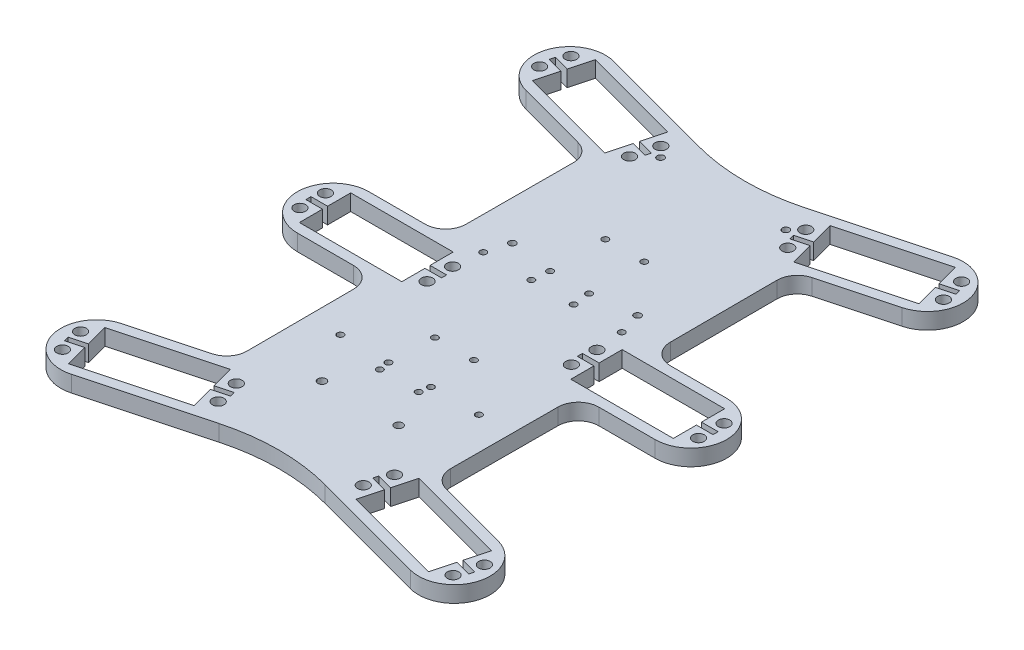
SolidWorks part; units mm, degrees
ref_plane "Front Plane" through (0, 0, 0) normal (0, 0, 1) x (1, 0, 0)
ref_plane "Top Plane" through (0, 0, 0) normal (0, 1, 0) x (1, 0, 0)
ref_plane "Right Plane" through (0, 0, 0) normal (1, 0, 0) x (0, 0, -1)
sketch "Sketch1" plane through (0, 0, 0) normal (0, 1, 0) x (1, 0, 0)
  line L0 (0, 32.1883) -> (0, -21.4181) construction
  line L1 (0, 0) -> (27.1703, 0) construction
  line L2 (-70, 14) -> (-40, 14)
  line L3 (-40, 14) -> (-39.8161, 70)
  line L4 (-39.8161, 70) -> (-73.6235, 79.0587)
  line L5 (-66.3765, 106.1046) -> (0, 88.3191)
  line L10 (-66.3765, 106.1046) -> (-73.6235, 79.0587) construction
  line L12 (-70, 14) -> (-70, -14) construction
  line L14 (-66.3765, -106.1046) -> (0, -88.3191)
  line L15 (-39.8161, -70) -> (-73.6235, -79.0587)
  line L16 (-40, -14) -> (-39.8161, -70)
  line L17 (-70, -14) -> (-40, -14)
  line L18 (66.3765, -106.1046) -> (0, -88.3191)
  line L19 (66.3765, 106.1046) -> (0, 88.3191)
  line L20 (70, 14) -> (70, -14) construction
  line L21 (66.3765, 106.1046) -> (73.6235, 79.0587) construction
  line L22 (70, -14) -> (40, -14)
  line L23 (40, -14) -> (39.8161, -70)
  line L24 (39.8161, -70) -> (73.6235, -79.0587)
  line L25 (39.8161, 70) -> (73.6235, 79.0587)
  line L26 (40, 14) -> (39.8161, 70)
  line L27 (70, 14) -> (40, 14)
  line L28 (-70.4609, 103.1096) -> (-75.6631, 83.6945)
  line L29 (-75.6631, 83.6945) -> (-36.9295, 73.3159)
  line L30 (-36.9295, 73.3159) -> (-31.7272, 92.731)
  line L31 (-31.7272, 92.731) -> (-70.4609, 103.1096)
  line L32 (-51.094, 97.9203) -> (-56.2963, 78.5052) construction
  line L33 (-70, 92.5816) -> (-73.062, 93.4021) construction
  line L34 (-53.12, 10.05) -> (-53.12, -10.05) construction
  line L35 (-73.17, 10.05) -> (-33.07, 10.05)
  line L36 (-73.17, 10.05) -> (-73.17, -10.05)
  line L37 (-73.17, -10.05) -> (-33.07, -10.05)
  line L38 (-33.07, 10.05) -> (-33.07, -10.05)
  line L39 (-73.17, 10.05) -> (-33.07, -10.05) construction
  line L40 (-73.17, -10.05) -> (-33.07, 10.05) construction
  line L41 (-36.9295, -73.3159) -> (-31.7272, -92.731)
  line L42 (-31.7272, -92.731) -> (-70.4609, -103.1096)
  line L43 (-70.4609, -103.1096) -> (-75.6631, -83.6945)
  line L44 (-75.6631, -83.6945) -> (-36.9295, -73.3159)
  line L45 (36.9295, 73.3159) -> (31.7272, 92.731)
  line L46 (75.6631, 83.6945) -> (36.9295, 73.3159)
  line L47 (70.4609, 103.1096) -> (75.6631, 83.6945)
  line L48 (31.7272, 92.731) -> (70.4609, 103.1096)
  line L49 (73.17, -10.05) -> (33.07, 10.05) construction
  line L50 (73.17, 10.05) -> (33.07, -10.05) construction
  line L51 (53.12, 10.05) -> (53.12, -10.05) construction
  line L52 (33.07, 10.05) -> (33.07, -10.05)
  line L53 (73.17, -10.05) -> (33.07, -10.05)
  line L54 (73.17, 10.05) -> (73.17, -10.05)
  line L55 (73.17, 10.05) -> (33.07, 10.05)
  line L56 (36.9295, -73.3159) -> (31.7272, -92.731)
  line L57 (75.6631, -83.6945) -> (36.9295, -73.3159)
  line L58 (31.7272, -92.731) -> (70.4609, -103.1096)
  line L59 (70.4609, -103.1096) -> (75.6631, -83.6945)
  line L60 (-76.4333, 99.4818) -> (-79.0215, 89.8226) construction
  line L61 (-77.7274, 94.6522) -> (-70, 92.5816) construction
  line L62 (-78, 5) -> (-78, -5) construction
  arc A0 (-70, 14) -> (-70, -14) centre (-70, 0) ccw
  arc A1 (-66.3765, 106.1046) -> (-73.6235, 79.0587) centre (-70, 92.5816) ccw
  circle A8 centre (-76.4333, 99.4818) radius 2.25
  circle A9 centre (-79.0215, 89.8226) radius 2.25
  circle A10 centre (-78, 5) radius 2.25
  arc A11 (-66.3765, -106.1046) -> (-73.6235, -79.0587) centre (-70, -92.5816) cw
  circle A12 centre (-79.0215, -89.8226) radius 2.25
  circle A13 centre (-76.4333, -99.4818) radius 2.25
  circle A14 centre (-78, -5) radius 2.25
  circle A15 centre (78, -5) radius 2.25
  circle A16 centre (76.4333, -99.4818) radius 2.25
  circle A17 centre (79.0215, -89.8226) radius 2.25
  arc A18 (66.3765, -106.1046) -> (73.6235, -79.0587) centre (70, -92.5816) ccw
  circle A19 centre (78, 5) radius 2.25
  circle A20 centre (79.0215, 89.8226) radius 2.25
  circle A21 centre (76.4333, 99.4818) radius 2.25
  arc A22 (66.3765, 106.1046) -> (73.6235, 79.0587) centre (70, 92.5816) cw
  arc A23 (70, 14) -> (70, -14) centre (70, 0) cw
  circle A24 centre (-30.957, 76.9437) radius 2.25
  circle A25 centre (-28.3688, 86.603) radius 2.25
  circle A26 centre (-28.24, -5) radius 2.25
  circle A27 centre (-28.24, 5) radius 2.25
  circle A28 centre (-28.3688, -86.603) radius 2.25
  circle A29 centre (-30.957, -76.9437) radius 2.25
  circle A30 centre (28.3688, 86.603) radius 2.25
  circle A31 centre (30.957, 76.9437) radius 2.25
  circle A32 centre (28.24, 5) radius 2.25
  circle A33 centre (28.24, -5) radius 2.25
  circle A34 centre (30.957, -76.9437) radius 2.25
  circle A35 centre (28.3688, -86.603) radius 2.25
  point P60 (-51.094, 97.9203)
  point P62 (-56.2963, 78.5052)
  point P65 (-73.062, 93.4021)
  point P71 (-53.12, 0)
  point P108 (53.12, 0)
  point P118 (-83.523, 96.2051)
  dimension "D2" = 14
  dimension "D3" = 10
  dimension "D8" = 4.5
  dimension "D1" = 75
  dimension "D4" = 70
  dimension "D5" = 30
  dimension "D6" = 35
  dimension "D7" = 56
  dimension "D9" = 8
  dimension "D10" = 5
  dimension "D11" = 10
  dimension "D12" = 40.1
  dimension "D13" = 20.1
  dimension "D14" = 4.83
  dimension "D15" = 40.1
  dimension "D16" = 20.1
  dimension "D17" = 4.83
  dimension "D18" = 8
extrude "Boss-Extrude1" add sketch "Sketch1" along normal blind 6.35
fillet "Fillet1" radius 80 2 edges at (0, 3.175, -88.3191) (0, 3.175, 88.3191)
fillet "Fillet2" radius 8 8 edges at (39.8161, 3.175, 70) (40, 3.175, 14) (40, 3.175, -14) (39.8161, 3.175, -70) (-39.8161, 3.175, -70) (-40, 3.175, -14) (-40, 3.175, 14) (-39.8161, 3.175, 70)
sketch "Sketch5" plane through (0, 6.35, 0) normal (0, 1, 0) x (1, 0, 0)
  line L0 (0, 91.1411) -> (0, -91.1411) construction
  line L1 (-84, 0) -> (84, 0) construction
  line L2 (-33.07, -10.05) -> (-33.07, 10.05) construction
  line L3 (-33.07, 1) -> (-26.57, 1)
  line L4 (-33.07, 1) -> (-33.07, -1)
  line L5 (-33.07, -1) -> (-26.57, -1)
  line L6 (-26.57, 1) -> (-26.57, -1)
  line L7 (-33.07, 1) -> (-26.57, -1) construction
  line L8 (-33.07, -1) -> (-26.57, 1) construction
  line L9 (-33.07, 10.05) -> (-73.17, 10.05) construction
  line L10 (-53.12, 10.05) -> (-53.12, -10.05) construction
  line L11 (-73.17, -10.05) -> (-33.07, -10.05) construction
  line L12 (-73.17, -1) -> (-79.67, 1) construction
  line L13 (-73.17, 1) -> (-79.67, -1) construction
  line L14 (-79.67, 1) -> (-79.67, -1)
  line L15 (-73.17, -1) -> (-79.67, -1)
  line L16 (-73.17, 1) -> (-73.17, -1)
  line L17 (-73.17, 1) -> (-79.67, 1)
  line L18 (-34.0695, 83.9894) -> (-27.791, 82.307)
  line L19 (-36.9295, 73.3159) -> (-31.7272, 92.731) construction
  line L20 (-27.791, 82.307) -> (-28.3087, 80.3752)
  line L21 (-28.3087, 80.3752) -> (-34.5872, 82.0575)
  line L22 (-34.0695, 83.9894) -> (-34.5872, 82.0575)
  line L23 (-51.094, 97.9203) -> (-56.2963, 78.5052) construction
  line L24 (-31.7272, 92.731) -> (-70.4609, 103.1096) construction
  line L25 (-75.6631, 83.6945) -> (-36.9295, 73.3159) construction
  line L26 (-72.8032, 94.368) -> (-73.3208, 92.4362)
  line L27 (-79.5993, 94.1185) -> (-73.3208, 92.4362)
  line L28 (-79.0817, 96.0503) -> (-79.5993, 94.1185)
  line L29 (-72.8032, 94.368) -> (-79.0817, 96.0503)
  line L30 (51.094, 97.9203) -> (56.2963, 78.5052) construction
  line L31 (72.8032, 94.368) -> (79.0817, 96.0503)
  line L32 (79.0817, 96.0503) -> (79.5993, 94.1185)
  line L33 (79.5993, 94.1185) -> (73.3208, 92.4362)
  line L34 (72.8032, 94.368) -> (73.3208, 92.4362)
  line L35 (34.0695, 83.9894) -> (34.5872, 82.0575)
  line L36 (28.3087, 80.3752) -> (34.5872, 82.0575)
  line L37 (27.791, 82.307) -> (28.3087, 80.3752)
  line L38 (34.0695, 83.9894) -> (27.791, 82.307)
  line L39 (73.17, 1) -> (79.67, -1) construction
  line L40 (73.17, -1) -> (79.67, 1) construction
  line L41 (53.12, 10.05) -> (53.12, -10.05) construction
  line L42 (33.07, -1) -> (26.57, 1) construction
  line L43 (33.07, 1) -> (26.57, -1) construction
  line L44 (73.17, 1) -> (79.67, 1)
  line L45 (73.17, 1) -> (73.17, -1)
  line L46 (73.17, -1) -> (79.67, -1)
  line L47 (79.67, 1) -> (79.67, -1)
  line L48 (26.57, 1) -> (26.57, -1)
  line L49 (33.07, -1) -> (26.57, -1)
  line L50 (33.07, 1) -> (33.07, -1)
  line L51 (33.07, 1) -> (26.57, 1)
  line L52 (51.094, -97.9203) -> (56.2963, -78.5052) construction
  line L53 (-51.094, -97.9203) -> (-56.2963, -78.5052) construction
  line L54 (34.0695, -83.9894) -> (27.791, -82.307)
  line L55 (27.791, -82.307) -> (28.3087, -80.3752)
  line L56 (28.3087, -80.3752) -> (34.5872, -82.0575)
  line L57 (34.0695, -83.9894) -> (34.5872, -82.0575)
  line L58 (72.8032, -94.368) -> (73.3208, -92.4362)
  line L59 (79.5993, -94.1185) -> (73.3208, -92.4362)
  line L60 (79.0817, -96.0503) -> (79.5993, -94.1185)
  line L61 (72.8032, -94.368) -> (79.0817, -96.0503)
  line L62 (-72.8032, -94.368) -> (-79.0817, -96.0503)
  line L63 (-79.0817, -96.0503) -> (-79.5993, -94.1185)
  line L64 (-79.5993, -94.1185) -> (-73.3208, -92.4362)
  line L65 (-72.8032, -94.368) -> (-73.3208, -92.4362)
  line L66 (-34.0695, -83.9894) -> (-34.5872, -82.0575)
  line L67 (-28.3087, -80.3752) -> (-34.5872, -82.0575)
  line L68 (-27.791, -82.307) -> (-28.3087, -80.3752)
  line L69 (-34.0695, -83.9894) -> (-27.791, -82.307)
  arc A0 (-20.7055, 93.8671) -> (20.7055, 93.8671) centre (0, 171.1411) ccw construction
  arc A1 (20.7055, -93.8671) -> (-20.7055, -93.8671) centre (0, -171.1411) ccw construction
  arc A2 (-70, 14) -> (-70, -14) centre (-70, 0) ccw construction
  arc A3 (70, -14) -> (70, 14) centre (70, 0) ccw construction
  point P16 (-29.82, 0)
  point P23 (-53.12, 10.05)
  point P34 (-76.42, 0)
  point P39 (-34.3284, 83.0234)
  point P42 (-34.3284, 83.0234)
  point P53 (-73.062, 93.4021)
  point P64 (73.062, 93.4021)
  point P65 (34.3284, 83.0234)
  point P76 (76.42, 0)
  point P77 (29.82, 0)
  point P98 (34.3284, -83.0234)
  point P99 (73.062, -93.4021)
  point P100 (-73.062, -93.4021)
  point P101 (-34.3284, -83.0234)
  dimension "D1" = 2
  dimension "D2" = 6.5
  dimension "D3" = 2
  dimension "D4" = 6.5
extrude "Cut-Extrude2" cut sketch "Sketch5" against normal through all
sketch "Sketch6" plane through (0, 6.35, 0) normal (0, 1, 0) x (1, 0, 0)
  circle A0 centre (27.1, -40.0589) radius 1.25 construction
  circle A1 centre (8.3, -40.0589) radius 1.25 construction
  circle A2 centre (-8.3, -40.0589) radius 1.25 construction
  circle A3 centre (-27.1, -40.0589) radius 1.25 construction
  circle A4 centre (27.1, 15.8411) radius 1.25 construction
  circle A5 centre (-8.3, 15.8411) radius 1.25 construction
  circle A6 centre (-27.1, 15.8411) radius 1.25 construction
  circle A7 centre (-24.5, 24.6411) radius 1.35 construction
  circle A8 centre (24.5, 24.6411) radius 1.35 construction
  circle A9 centre (24.5, 82.6411) radius 1.35 construction
  circle A10 centre (-24.5, 82.6411) radius 1.35 construction
  circle A11 centre (27.1, -40.0589) radius 1.25
  circle A12 centre (8.3, -40.0589) radius 1.25
  circle A13 centre (-8.3, -40.0589) radius 1.25
  circle A14 centre (-27.1, -40.0589) radius 1.25
  circle A15 centre (27.1, 15.8411) radius 1.25
  circle A16 centre (-8.3, 15.8411) radius 1.25
  circle A17 centre (-27.1, 15.8411) radius 1.25
  circle A18 centre (-24.5, 24.6411) radius 1.35
  circle A19 centre (24.5, 24.6411) radius 1.35
  circle A20 centre (24.5, 82.6411) radius 1.35
  circle A21 centre (-24.5, 82.6411) radius 1.35
  circle A22 centre (8.3, 15.8411) radius 1.25 construction
  circle A23 centre (8.3, 15.8411) radius 1.25
extrude "Cut-Extrude3" cut sketch "Sketch6" against normal blind 10
sketch "Sketch7" plane through (0, 0, 0) normal (0, -1, 0) x (1, 0, 0)
  circle A0 centre (-7.62, 44.13) radius 1.25 construction
  circle A1 centre (7.62, 44.13) radius 1.25 construction
  circle A2 centre (7.62, 22.54) radius 1.25 construction
  circle A3 centre (-7.62, 22.54) radius 1.25 construction
  circle A4 centre (7.62, -22.54) radius 1.25 construction
  circle A5 centre (7.62, -44.13) radius 1.25 construction
  circle A6 centre (-7.62, -22.54) radius 1.25 construction
  circle A7 centre (-7.62, -44.13) radius 1.25 construction
  circle A8 centre (-7.62, 44.13) radius 1.25
  circle A9 centre (7.62, 44.13) radius 1.25
  circle A10 centre (7.62, 22.54) radius 1.25
  circle A11 centre (-7.62, 22.54) radius 1.25
  circle A12 centre (7.62, -22.54) radius 1.25
  circle A13 centre (7.62, -44.13) radius 1.25
  circle A14 centre (-7.62, -22.54) radius 1.25
  circle A15 centre (-7.62, -44.13) radius 1.25
extrude "Cut-Extrude4" cut sketch "Sketch7" against normal blind 10
sketch "Sketch8" plane through (0, 6.35, 0) normal (0, 1, 0) x (1, 0, 0)
  circle A0 centre (15, -59.3589) radius 1.6 construction
  circle A1 centre (-15, -59.3589) radius 1.6 construction
  circle A2 centre (15, -59.3589) radius 1.6
  circle A3 centre (-15, -59.3589) radius 1.6
extrude "Cut-Extrude5" cut sketch "Sketch8" against normal blind 10
